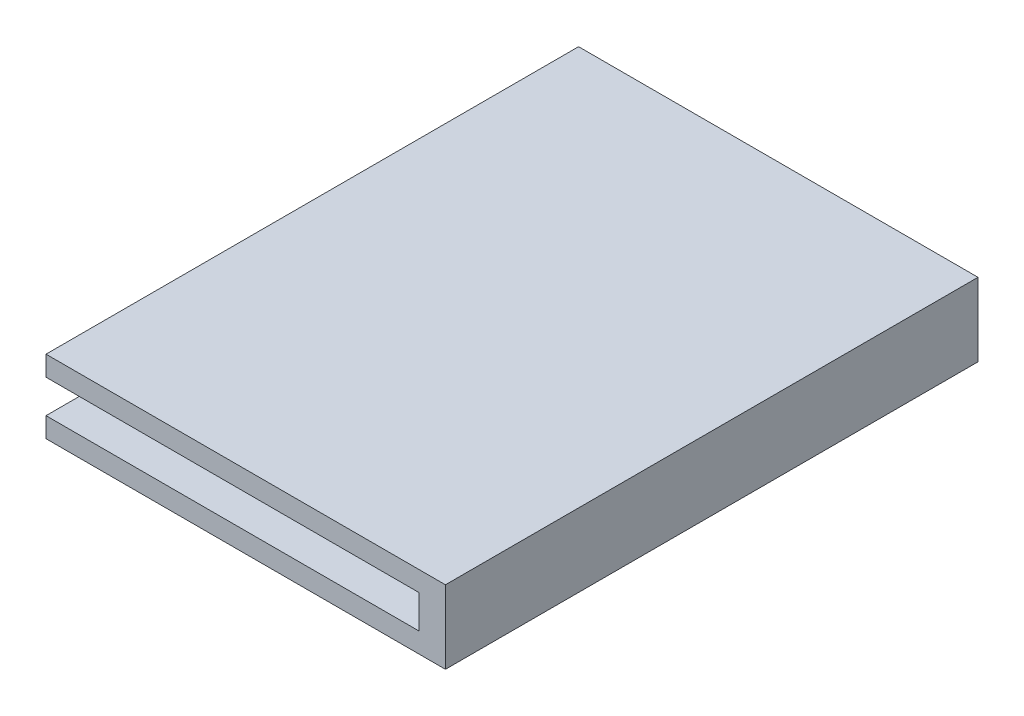
SolidWorks part; units mm, degrees
ref_plane "Přední rovina" through (0, 0, 0) normal (0, 0, 1) x (1, 0, 0)
ref_plane "Horní rovina" through (0, 0, 0) normal (0, 1, 0) x (1, 0, 0)
ref_plane "Pravá rovina" through (0, 0, 0) normal (1, 0, 0) x (0, 0, -1)
sketch "Skica1" plane through (0, 0, 0) normal (0, 0, 1) x (1, 0, 0)
  line L0 (0, 0) -> (0, -5)
  line L1 (0, -5) -> (-56, -5)
  line L2 (-56, -5) -> (-56, -8)
  line L3 (-56, -8) -> (4, -8)
  line L4 (4, -8) -> (4, 3)
  line L5 (4, 3) -> (-56, 3)
  line L6 (-56, 3) -> (-56, 0)
  line L7 (-56, 0) -> (0, 0)
  dimension "D1" = 5
  dimension "D2" = 3
  dimension "D3" = 3
  dimension "D4" = 4
  dimension "D5" = 60
extrude "Přidat vysunutím1" add sketch "Skica1" along normal blind 80
